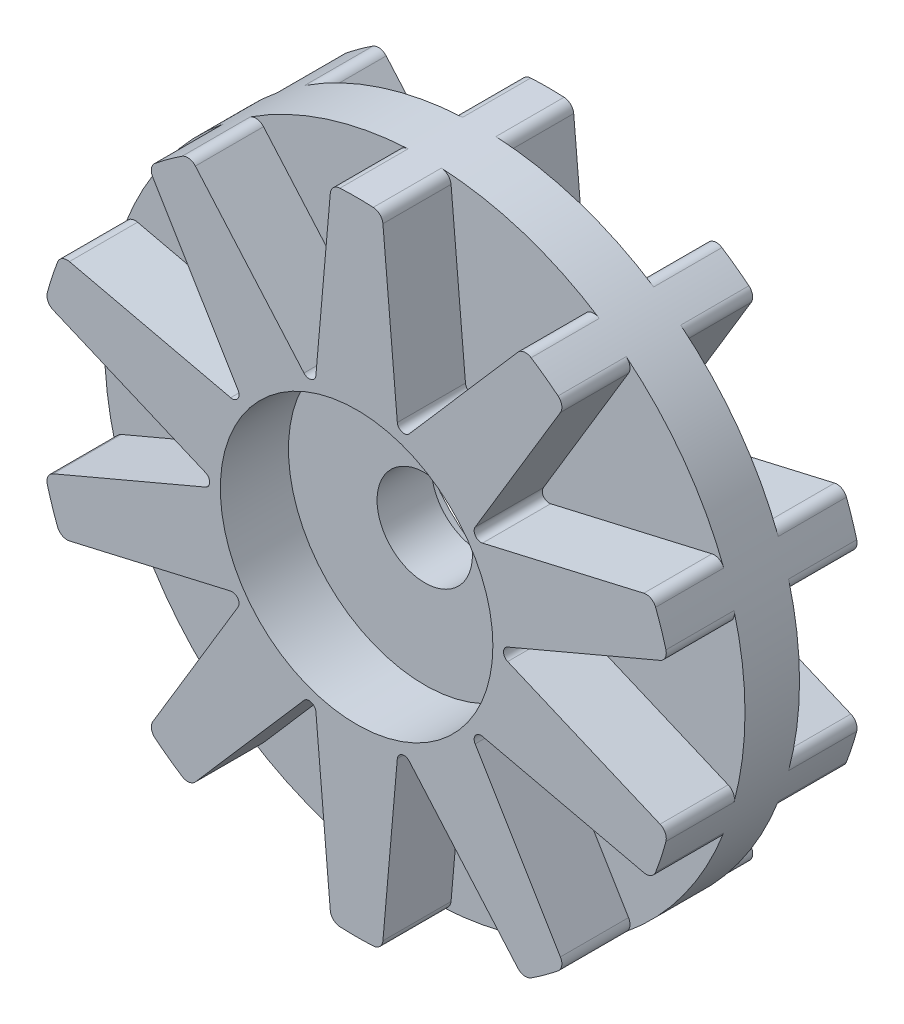
SolidWorks part; units mm, degrees
ref_plane "Piano frontale" through (0, 0, 0) normal (0, 0, 1) x (1, 0, 0)
ref_plane "Piano superiore" through (0, 0, 0) normal (0, 1, 0) x (1, 0, 0)
ref_plane "Piano destro" through (0, 0, 0) normal (1, 0, 0) x (0, 0, -1)
sketch "Schizzo1" plane through (0, 0, 0) normal (0, 0, 1) x (1, 0, 0)
  circle A0 centre (0, 0) radius 94
  circle A1 centre (0, 0) radius 14
  dimension "D1" = 188
  dimension "D2" = 28
extrude "Estrusione-Estrusione1" add sketch "Schizzo1" along normal blind 16
sketch "Schizzo2" plane through (0, 0, 16) normal (0, 0, 1) x (1, 0, 0)
  line L0 (0, 0) -> (0, 93.7003) construction
  line L1 (-7.5, 93.7003) -> (7.5, 93.7003) construction
  line L2 (0, 0) -> (-12.3607, 38.0423) construction
  line L3 (-7.7238, 91.1377) -> (-11.9506, 42.7381)
  line L4 (0, 0) -> (12.3607, 38.0423) construction
  line L5 (7.7238, 91.1377) -> (11.9506, 42.7381)
  line L6 (59.8181, 69.192) -> (34.7891, 27.5515)
  line L7 (-12.3607, 38.0423) -> (-11.9506, 42.7381) construction
  line L8 (-12.3607, 38.0423) -> (-13.943, 42.9121) construction
  line L9 (11.9506, 42.7381) -> (12.3607, 38.0423) construction
  line L10 (12.3607, 38.0423) -> (13.943, 42.9121) construction
  line L11 (47.3207, 78.2719) -> (15.4526, 41.6003)
  line L12 (0, 0) -> (55.0757, 75.8052) construction
  line L13 (49.008, 80.2135) -> (61.1433, 71.3968) construction
  line L14 (89.0639, 20.8173) -> (44.3393, 1.8411)
  line L15 (84.2903, 35.5089) -> (36.9535, 24.5725)
  line L16 (0, 0) -> (89.1143, 28.955) construction
  line L17 (86.7967, 36.0879) -> (91.4319, 21.8221) construction
  line L18 (84.2903, -35.5089) -> (36.9535, -24.5725)
  line L19 (89.0639, -20.8173) -> (44.3393, -1.8411)
  line L20 (0, 0) -> (89.1143, -28.955) construction
  line L21 (91.4319, -21.8221) -> (86.7967, -36.0879) construction
  line L22 (47.3207, -78.2719) -> (15.4526, -41.6003)
  line L23 (59.8181, -69.192) -> (34.7891, -27.5515)
  line L24 (0, 0) -> (55.0757, -75.8052) construction
  line L25 (61.1433, -71.3968) -> (49.008, -80.2135) construction
  line L26 (-7.7238, -91.1377) -> (-11.9506, -42.7381)
  line L27 (7.7238, -91.1377) -> (11.9506, -42.7381)
  line L28 (0, 0) -> (0, -93.7003) construction
  line L29 (7.5, -93.7003) -> (-7.5, -93.7003) construction
  line L30 (-59.8181, -69.192) -> (-34.7891, -27.5515)
  line L31 (-47.3207, -78.2719) -> (-15.4526, -41.6003)
  line L32 (0, 0) -> (-55.0757, -75.8052) construction
  line L33 (-49.008, -80.2135) -> (-61.1433, -71.3968) construction
  line L34 (-89.0639, -20.8173) -> (-44.3393, -1.8411)
  line L35 (-84.2903, -35.5089) -> (-36.9535, -24.5725)
  line L36 (0, 0) -> (-89.1143, -28.955) construction
  line L37 (-86.7967, -36.0879) -> (-91.4319, -21.8221) construction
  line L38 (-84.2903, 35.5089) -> (-36.9535, 24.5725)
  line L39 (-89.0639, 20.8173) -> (-44.3393, 1.8411)
  line L40 (0, 0) -> (-89.1143, 28.955) construction
  line L41 (-91.4319, 21.8221) -> (-86.7967, 36.0879) construction
  line L42 (-47.3207, 78.2719) -> (-15.4526, 41.6003)
  line L43 (-59.8181, 69.192) -> (-34.7891, 27.5515)
  line L44 (0, 0) -> (-55.0757, 75.8052) construction
  line L45 (-61.1433, 71.3968) -> (-49.008, 80.2135) construction
  arc A0 (11.9506, 42.7381) -> (13.325, 41.01) centre (13.943, 42.9121) ccw
  circle A1 centre (0, 0) radius 40
  circle A13 centre (0, 0) radius 94 construction
  arc A14 (4.8913, 93.8727) -> (-4.8913, 93.8727) centre (0, 0) ccw
  arc A15 (-13.325, 41.01) -> (-11.9506, 42.7381) centre (-13.943, 42.9121) ccw
  arc A16 (4.8913, 93.8727) -> (7.7238, 91.1377) centre (4.7352, 90.8767) cw
  arc A17 (-4.8913, 93.8727) -> (-7.7238, 91.1377) centre (-4.7352, 90.8767) ccw
  circle A19 centre (0, 0) radius 43.1205 construction
  arc A20 (59.1341, 73.0696) -> (59.8181, 69.192) centre (57.2468, 70.7375) cw
  arc A21 (59.1341, 73.0696) -> (51.2198, 78.8196) centre (0, 0) ccw
  arc A22 (51.2198, 78.8196) -> (47.3207, 78.2719) centre (49.5852, 76.3041) ccw
  arc A23 (13.325, 41.01) -> (15.4526, 41.6003) centre (13.943, 42.9121) ccw
  arc A24 (34.7891, 27.5515) -> (34.8852, 25.3456) centre (36.5032, 26.5212) ccw
  arc A25 (90.7897, 24.3564) -> (89.0639, 20.8173) centre (87.8921, 23.579) cw
  arc A26 (90.7897, 24.3564) -> (87.7667, 33.6601) centre (0, 0) ccw
  arc A27 (87.7667, 33.6601) -> (84.2903, 35.5089) centre (84.9656, 32.5859) ccw
  arc A28 (34.8852, 25.3456) -> (36.9535, 24.5725) centre (36.5032, 26.5212) ccw
  arc A29 (44.3393, 1.8411) -> (43.1205, 0) centre (45.1205, 0) ccw
  arc A30 (87.7667, -33.6601) -> (84.2903, -35.5089) centre (84.9656, -32.5859) cw
  arc A31 (87.7667, -33.6601) -> (90.7897, -24.3564) centre (0, 0) ccw
  arc A32 (90.7897, -24.3564) -> (89.0639, -20.8173) centre (87.8921, -23.579) ccw
  arc A33 (43.1205, 0) -> (44.3393, -1.8411) centre (45.1205, 0) ccw
  arc A34 (36.9535, -24.5725) -> (34.8852, -25.3456) centre (36.5032, -26.5212) ccw
  arc A35 (51.2198, -78.8196) -> (47.3207, -78.2719) centre (49.5852, -76.3041) cw
  arc A36 (51.2198, -78.8196) -> (59.1341, -73.0696) centre (0, 0) ccw
  arc A37 (59.1341, -73.0696) -> (59.8181, -69.192) centre (57.2468, -70.7375) ccw
  arc A38 (34.8852, -25.3456) -> (34.7891, -27.5515) centre (36.5032, -26.5212) ccw
  arc A39 (15.4526, -41.6003) -> (13.325, -41.01) centre (13.943, -42.9121) ccw
  arc A40 (-4.8913, -93.8727) -> (-7.7238, -91.1377) centre (-4.7352, -90.8767) cw
  arc A41 (-4.8913, -93.8727) -> (4.8913, -93.8727) centre (0, 0) ccw
  arc A42 (4.8913, -93.8727) -> (7.7238, -91.1377) centre (4.7352, -90.8767) ccw
  arc A43 (13.325, -41.01) -> (11.9506, -42.7381) centre (13.943, -42.9121) ccw
  arc A44 (-11.9506, -42.7381) -> (-13.325, -41.01) centre (-13.943, -42.9121) ccw
  arc A45 (-59.1341, -73.0696) -> (-59.8181, -69.192) centre (-57.2468, -70.7375) cw
  arc A46 (-59.1341, -73.0696) -> (-51.2198, -78.8196) centre (0, 0) ccw
  arc A47 (-51.2198, -78.8196) -> (-47.3207, -78.2719) centre (-49.5852, -76.3041) ccw
  arc A48 (-13.325, -41.01) -> (-15.4526, -41.6003) centre (-13.943, -42.9121) ccw
  arc A49 (-34.7891, -27.5515) -> (-34.8852, -25.3456) centre (-36.5032, -26.5212) ccw
  arc A50 (-90.7897, -24.3564) -> (-89.0639, -20.8173) centre (-87.8921, -23.579) cw
  arc A51 (-90.7897, -24.3564) -> (-87.7667, -33.6601) centre (0, 0) ccw
  arc A52 (-87.7667, -33.6601) -> (-84.2903, -35.5089) centre (-84.9656, -32.5859) ccw
  arc A53 (-34.8852, -25.3456) -> (-36.9535, -24.5725) centre (-36.5032, -26.5212) ccw
  arc A54 (-44.3393, -1.8411) -> (-43.1205, 0) centre (-45.1205, 0) ccw
  arc A55 (-87.7667, 33.6601) -> (-84.2903, 35.5089) centre (-84.9656, 32.5859) cw
  arc A56 (-87.7667, 33.6601) -> (-90.7897, 24.3564) centre (0, 0) ccw
  arc A57 (-90.7897, 24.3564) -> (-89.0639, 20.8173) centre (-87.8921, 23.579) ccw
  arc A58 (-43.1205, 0) -> (-44.3393, 1.8411) centre (-45.1205, 0) ccw
  arc A59 (-36.9535, 24.5725) -> (-34.8852, 25.3456) centre (-36.5032, 26.5212) ccw
  arc A60 (-51.2198, 78.8196) -> (-47.3207, 78.2719) centre (-49.5852, 76.3041) cw
  arc A61 (-51.2198, 78.8196) -> (-59.1341, 73.0696) centre (0, 0) ccw
  arc A62 (-59.1341, 73.0696) -> (-59.8181, 69.192) centre (-57.2468, 70.7375) ccw
  arc A63 (-34.8852, 25.3456) -> (-34.7891, 27.5515) centre (-36.5032, 26.5212) ccw
  arc A64 (-15.4526, 41.6003) -> (-13.325, 41.01) centre (-13.943, 42.9121) ccw
  point P6 (0, 93.7003)
  point P162 (0, 0)
  circle M69 centre (0, 0) radius 94
  dimension "D3" = 80
  dimension "D5" = 4
  dimension "D6" = 3
  dimension "D2" = 18
  dimension "D1" = 15
  dimension "D4" = 36
extrude "Estrusione-Estrusione2" add sketch "Schizzo2" along normal blind 20 contours A64 L42 A60 A62 L43 A63 A59 L38 A55 A57 L39 A58 A54 L34 A50 A52 L35 A53 A49 L30 A45 A47 L31 A48 A44 L26 A40 A42 L27 A43 A39 L22 A35 A37 L23 A38 A34 L18 A30 A32 L19 A33 A29 L14 M69
pattern_linear "Ripetizione a L1" count 2 spacing 36 along (0, 0, -1) of "Estrusione-Estrusione2"
